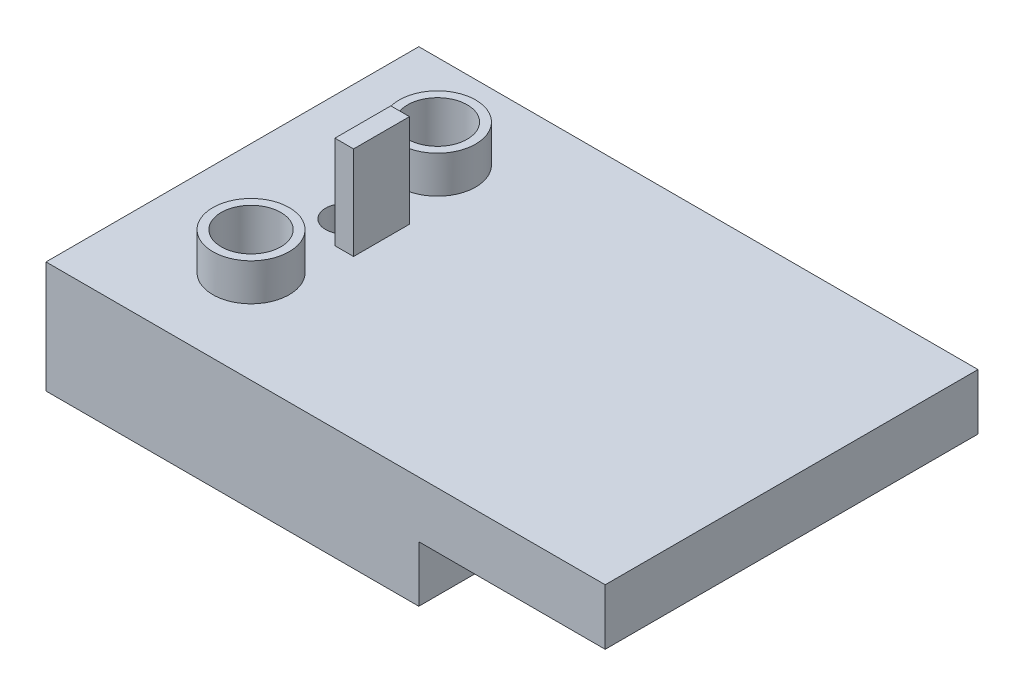
SolidWorks part; units mm, degrees
ref_plane "Alzado" through (0, 0, 0) normal (0, 0, 1) x (1, 0, 0)
ref_plane "Planta" through (0, 0, 0) normal (0, 1, 0) x (1, 0, 0)
ref_plane "Vista lateral" through (0, 0, 0) normal (1, 0, 0) x (0, 0, -1)
sketch "Croquis1" plane through (0, 0, 0) normal (0, 1, 0) x (1, 0, 0)
  line L1 (0, 0) -> (30, 0)
  line L2 (0, 0) -> (0, 20)
  line L3 (0, 20) -> (30, 20)
  line L4 (30, 0) -> (30, 20)
  dimension "D1" = 30
  dimension "D2" = 20
extrude "Saliente-Extruir1" add sketch "Croquis1" along normal blind 6
sketch "Croquis3" plane through (0, 6, 0) normal (0, 1, 0) x (1, 0, 0)
  line L0 (6, 0) -> (6, 5) construction
  line L1 (0, 0) -> (30, 0) construction
  line L2 (6, 5) -> (6, 15) construction
  line L3 (6, 15) -> (6, 20) construction
  line L4 (30, 20) -> (0, 20) construction
  line L5 (0, 20) -> (0, 0) construction
  circle A0 centre (6, 5) radius 1.6
  circle A1 centre (6, 15) radius 1.6
  dimension "D1" = 3.2
  dimension "D2" = 6
  dimension "D3" = 10
extrude "Cortar-Extruir2" cut sketch "Croquis3" against normal blind 40
sketch "Croquis4" plane through (0, 6, 0) normal (0, 1, 0) x (1, 0, 0)
  circle A0 centre (6, 15) radius 2.05
  circle A1 centre (6, 5) radius 2.05
  circle A2 centre (6, 5) radius 1.6 construction
  circle A3 centre (6, 15) radius 1.6 construction
  circle A4 centre (6, 5) radius 1.6
  circle A5 centre (6, 15) radius 1.6
  dimension "D1" = 4.1
extrude "Saliente-Extruir2" add sketch "Croquis4" along normal blind 2
sketch "Croquis5" plane through (0, 0, 0) normal (0, -1, 0) x (1, 0, 0)
  line L1 (9, -6.7321) -> (9, -3.2679)
  line L2 (9, -3.2679) -> (6, -1.5359)
  line L3 (6, -1.5359) -> (3, -3.2679)
  line L4 (3, -3.2679) -> (3, -6.7321)
  line L5 (3, -6.7321) -> (6, -8.4641)
  line L6 (6, -8.4641) -> (9, -6.7321)
  line L7 (9, -16.7321) -> (9, -13.2679)
  line L8 (9, -13.2679) -> (6, -11.5359)
  line L9 (6, -11.5359) -> (3, -13.2679)
  line L10 (3, -13.2679) -> (3, -16.7321)
  line L11 (3, -16.7321) -> (6, -18.4641)
  line L12 (6, -18.4641) -> (9, -16.7321)
  circle A0 centre (6, -5) radius 3 construction
  circle A1 centre (6, -15) radius 3 construction
  dimension "D1" = 6
extrude "Cortar-Extruir3" cut sketch "Croquis5" against normal blind 3
sketch "Croquis6" plane through (0, 0, 0) normal (0, 0, 1) x (1, 0, 0)
  line L0 (30, 6) -> (30, 0) construction
  line L1 (30, 0) -> (20, 0)
  line L2 (30, 0) -> (30, 3)
  line L3 (30, 3) -> (20, 3)
  line L4 (20, 0) -> (20, 3)
  point P7 (30, 3)
  dimension "D1" = 10
extrude "Cortar-Extruir4" cut sketch "Croquis6" against normal blind 24
sketch "Croquis7" plane through (0, 6, 0) normal (0, 1, 0) x (1, 0, 0)
  line L0 (0, 10) -> (30, 10) construction
  line L1 (0, 20) -> (0, 0) construction
  line L2 (30, 0) -> (30, 20) construction
  line L3 (6, 10) -> (6, 15) construction
  circle A0 centre (6, 10) radius 1
  point P8 (5.4288, 10)
  dimension "D1" = 2
extrude "Cortar-Extruir5" cut sketch "Croquis7" against normal blind 24
sketch "Croquis8" plane through (0, 6, 0) normal (0, 1, 0) x (1, 0, 0)
  line L0 (7, 10) -> (0, 10) construction
  line L1 (7, 8.5) -> (8, 8.5)
  line L2 (7, 8.5) -> (7, 11.5)
  line L3 (7, 11.5) -> (8, 11.5)
  line L4 (8, 8.5) -> (8, 11.5)
  line L5 (0, 20) -> (0, 0) construction
  circle A0 centre (6, 10) radius 1 construction
  dimension "D1" = 1
  dimension "D2" = 3
extrude "Saliente-Extruir3" add sketch "Croquis8" along normal blind 5
